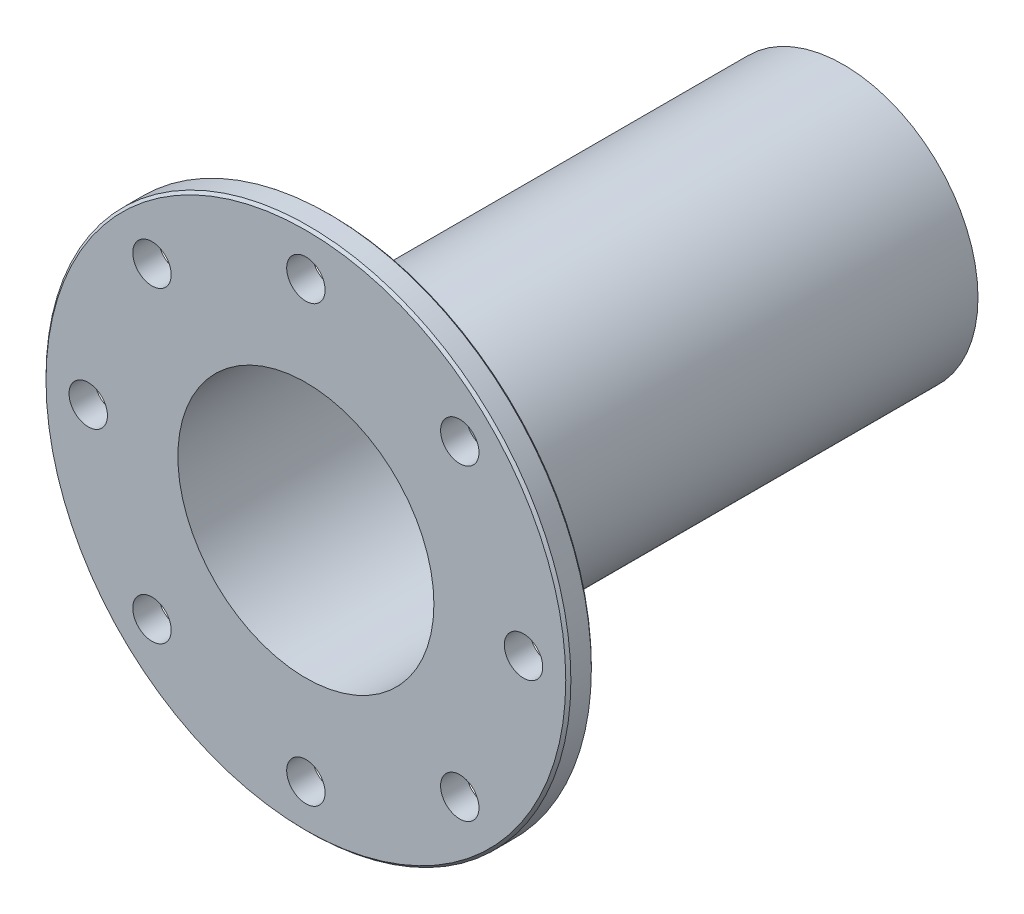
SolidWorks part; units mm, degrees
material "1023 Carbon Steel Sheet (SS)"
ref_plane "Front Plane" through (0, 0, 0) normal (0, 0, 1) x (1, 0, 0)
ref_plane "Top Plane" through (0, 0, 0) normal (0, 1, 0) x (1, 0, 0)
ref_plane "Right Plane" through (0, 0, 0) normal (1, 0, 0) x (0, 0, -1)
sketch "Sketch1" plane through (0, 0, 0) normal (1, 0, 0) x (0, 0, -1)
  line L0 (0, 100) -> (0, 205)
  line L1 (0, 205) -> (20, 205)
  line L2 (20, 205) -> (20, 105)
  line L3 (20, 105) -> (420, 105)
  line L4 (420, 105) -> (420, 100)
  line L5 (420, 100) -> (0, 100)
  line L6 (0, 0) -> (547.7347, 0) construction
  dimension "D1" = 20
  dimension "D2" = 400
  dimension "D3" = 5
  dimension "D4" = 100
  dimension "D5" = 100
revolve "Revolve1" add sketch "Sketch1" angle 360 about L6
sketch "Sketch2" plane through (0, 0, 0) normal (0, 0, 1) x (1, 0, 0)
  circle A0 centre (0, 170) radius 15
  circle A1 centre (0, 0) radius 205 construction
  circle A2 centre (120.2082, 120.2082) radius 15
  circle A3 centre (170, 0) radius 15
  circle A4 centre (120.2082, -120.2082) radius 15
  circle A5 centre (0, -170) radius 15
  circle A6 centre (-120.2082, -120.2082) radius 15
  circle A7 centre (-170, 0) radius 15
  circle A8 centre (-120.2082, 120.2082) radius 15
  point P21 (0, 0)
  dimension "D2" = 30
  dimension "D1" = 170
  dimension "D3" = 8
extrude "Cut-Extrude1" cut sketch "Sketch2" against normal up to surface (20 mm away) contours A8
chamfer "Chamfer1" distance 2 angle 45 2 edges at (205, 0, 0) (205, 0, -20)
